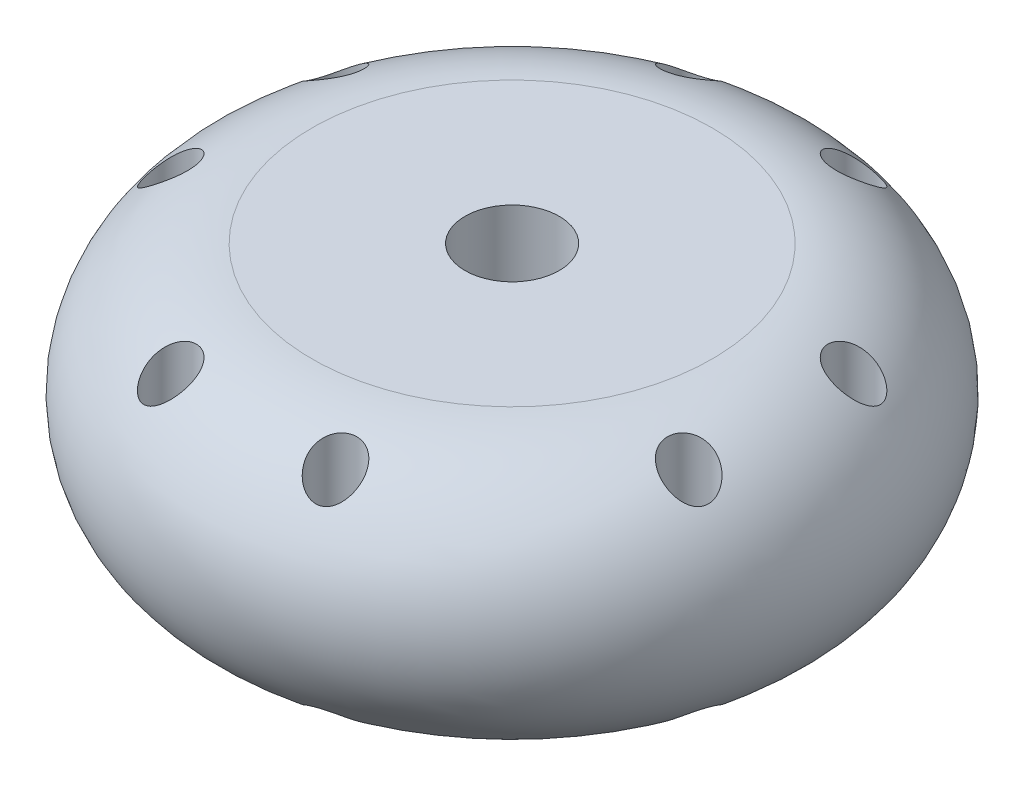
SolidWorks part; units mm, degrees
ref_plane "Front Plane" through (0, 0, 0) normal (0, 0, 1) x (1, 0, 0)
ref_plane "Top Plane" through (0, 0, 0) normal (0, 1, 0) x (1, 0, 0)
ref_plane "Right Plane" through (0, 0, 0) normal (1, 0, 0) x (0, 0, -1)
sketch "Sketch1" plane through (0, 0, 0) normal (0, 0, 1) x (1, 0, 0)
  line L0 (0, 0) -> (-17, 0)
  line L1 (-17, -22) -> (0, -22)
  line L2 (0, -22) -> (0, 0) construction
  line L3 (0, -22) -> (0, 0)
  arc A0 (-17, 0) -> (-17, -22) centre (-17, -11) ccw
  point P5 (-28, -11)
  dimension "D1" = 22
  dimension "D2" = 17
revolve "Revolve2" add sketch "Sketch1" angle 360 about L2
sketch "Sketch2" plane through (0, 0, 0) normal (0, 1, 0) x (1, 0, 0)
  line L0 (0, 0) -> (0, 28) construction
  circle A0 centre (7, 22) radius 2
  circle A1 centre (-7, 22) radius 2
  circle A2 centre (0, 0) radius 28 construction
  dimension "D1" = 4
  dimension "D2" = 7
  dimension "D3" = 7
  dimension "D4" = 22
extrude "Cut-Extrude1" cut sketch "Sketch2" against normal through all
pattern_circular "CirPattern1" count 4 over 360 about axis through (0, 0, 0) along (0, 1, 0) of "Cut-Extrude1"
sketch "Sketch3" plane through (0, 0, 0) normal (0, 1, 0) x (1, 0, 0)
  circle A0 centre (7, 0) radius 0.95
  dimension "D2" = 1.9
  dimension "D1" = 7
sketch "Sketch4" plane through (0, 0, 0) normal (0, 1, 0) x (1, 0, 0)
  circle A0 centre (0, 0) radius 4
  dimension "D1" = 8
extrude "Cut-Extrude3" cut sketch "Sketch4" against normal through all
sketch "Sketch5" plane through (0, -22, 0) normal (0, -1, 0) x (1, 0, 0)
  circle A0 centre (0, 0) radius 10.25
  dimension "D1" = 20.5
extrude "Cut-Extrude4" [suppressed] cut sketch "Sketch5" against normal blind 2.5
fillet "Fillet1" [suppressed] radius 1
